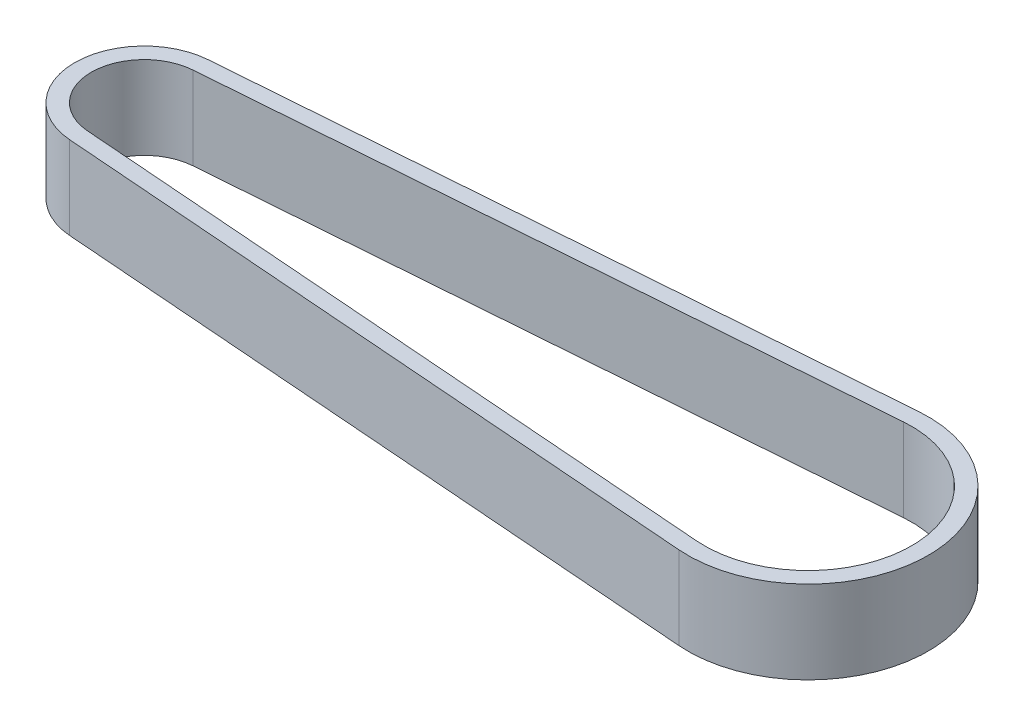
SolidWorks part; units mm, degrees
ref_plane "Front Plane" through (0, 0, 0) normal (0, 0, 1) x (1, 0, 0)
ref_plane "Top Plane" through (0, 0, 0) normal (0, 1, 0) x (1, 0, 0)
ref_plane "Right Plane" through (0, 0, 0) normal (1, 0, 0) x (0, 0, -1)
sketch "Sketch1" plane through (0, 0, 0) normal (0, 1, 0) x (1, 0, 0)
  line L0 (0, 0) -> (80, 0) construction
  line L1 (-0.4865, 6.3514) -> (79.0468, 12.4435)
  line L2 (-0.4865, -6.3514) -> (79.0468, -12.4435)
  line L3 (-0.6393, 8.3456) -> (78.8941, 14.4377)
  line L4 (-0.6393, -8.3456) -> (78.8941, -14.4377)
  arc A0 (-0.4865, 6.3514) -> (-0.4865, -6.3514) centre (0, 0) ccw
  arc A1 (79.0468, -12.4435) -> (79.0468, 12.4435) centre (80, 0) ccw
  arc A2 (78.8941, -14.4377) -> (78.8941, 14.4377) centre (80, 0) ccw
  arc A3 (-0.6393, 8.3456) -> (-0.6393, -8.3456) centre (0, 0) ccw
  dimension "D2" = 12.74
  dimension "D3" = 24.96
  dimension "D1" = 80
  dimension "D4" = 2
extrude "Boss-Extrude1" add sketch "Sketch1" along normal blind 10
